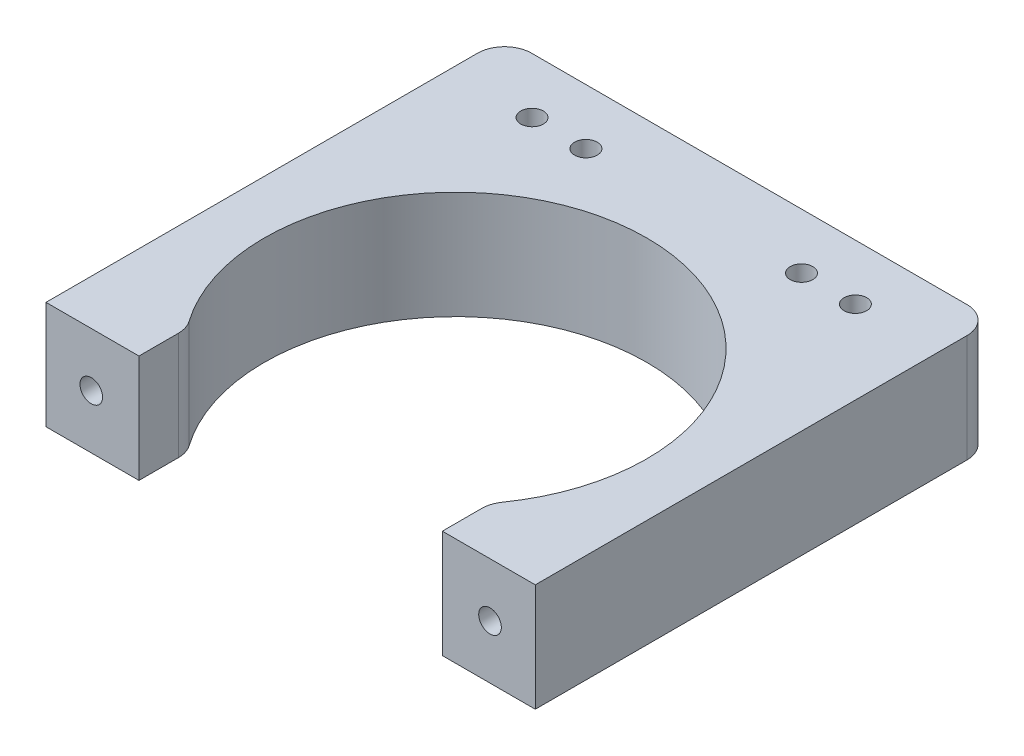
SolidWorks part; units mm, degrees
material "6061-T6 (SS)"
ref_plane "Front Plane" through (0, 0, 0) normal (0, 0, 1) x (1, 0, 0)
ref_plane "Top Plane" through (0, 0, 0) normal (0, 1, 0) x (1, 0, 0)
ref_plane "Right Plane" through (0, 0, 0) normal (1, 0, 0) x (0, 0, -1)
sketch "Sketch1" plane through (0, 0, 0) normal (0, 1, 0) x (1, 0, 0)
  line L0 (28.15, -42.55) -> (45.4, -42.55)
  line L1 (-45.4, 42.55) -> (45.4, 42.55)
  line L2 (-45.4, 42.55) -> (-45.4, -42.55)
  line L3 (-45.4, -42.55) -> (-28.15, -42.55)
  line L4 (45.4, 42.55) -> (45.4, -42.55)
  line L5 (-45.4, 42.55) -> (45.4, -42.55) construction
  line L6 (-45.4, -42.55) -> (45.4, 42.55) construction
  line L7 (-28.15, -42.55) -> (-28.15, -33.5793)
  line L8 (0, 0) -> (0, 42.55) construction
  line L9 (28.15, -42.55) -> (28.15, -33.5793)
  arc A0 (28.15, -33.5793) -> (-28.15, -33.5793) centre (0, -11.95) ccw
  point P0 (0, 0)
  dimension "D4" = 35.5
  dimension "D1" = 90.8
  dimension "D2" = 85.1
  dimension "D3" = 54.5
  dimension "D5" = 45.4
  dimension "D6" = 17.25
  dimension "D7" = 17.25
extrude "Boss-Extrude1" add sketch "Sketch1" along normal blind 20
sketch "Sketch3" plane through (0, 20, 0) normal (0, 1, 0) x (1, 0, 0)
  line L0 (45.4, 42.55) -> (-45.4, 42.55) construction
  line L1 (-45.4, 42.55) -> (-45.4, -42.55) construction
  line L2 (0, 0) -> (0, 50.4625) construction
  circle A0 centre (-30, 32.25) radius 2.1
  circle A1 centre (-20, 32.25) radius 2.1
  circle A2 centre (20, 32.25) radius 2.1
  circle A3 centre (30, 32.25) radius 2.1
  dimension "D1" = 4.2
  dimension "D2" = 10.3
  dimension "D3" = 15.4
  dimension "D4" = 10
extrude "Cut-Extrude1" cut sketch "Sketch3" against normal through all
sketch "Sketch4" plane through (0, 0, -42.55) normal (0, 0, -1) x (-1, 0, 0)
  line L0 (-45.4, 20) -> (-45.4, 0) construction
  line L1 (-45.4, 20) -> (45.4, 20) construction
  circle A0 centre (-30, 10) radius 2.1
  circle A1 centre (-10, 10) radius 2.1
  circle A2 centre (10, 10) radius 2.1
  circle A3 centre (30, 10) radius 2.1
  dimension "D1" = 4.2
  dimension "D2" = 15.4
  dimension "D3" = 10
  dimension "D4" = 4
hole_wizard "Ø4.2 (4.2) Diameter Hole1" positions "Sketch5" profile "Sketch6" hole size "Ø4.2" standard "ANSI Metric"
sketch "Sketch5" plane through (0, 0, -42.55) normal (0, 0, -1) x (-1, 0, 0)
  point P0 (-30, 10)
  point P3 (-10, 10)
  point P6 (10, 10)
  point P9 (30, 10)
sketch "Sketch6" plane through (30, 10, -42.55) normal (1, 0, 0) x (0, 1, 0)
  line L0 (0, 0) -> (0, 7.2618)
  line L1 (0, 7.2618) -> (2.1, 6)
  line L2 (2.1, 6) -> (2.1, 0)
  line L5 (2.1, 0) -> (0, 0)
  line L10 (0, 7.2618) -> (-2.1, 6) construction
  line L11 (0, -6.35) -> (0, 107.95) construction
  dimension "Hole Dia." = 4.2
  dimension "Hole Depth" = 6
  dimension "Drill Angle" = 118
sketch "Sketch14" plane through (-45.4, 0, 0) normal (-1, 0, 0) x (0, 0, 1)
  line L0 (-17.45, 20) -> (-17.45, 10)
  line L1 (-42.55, 20) -> (42.55, 20) construction
  line L3 (22.55, 20) -> (22.55, 10)
  line L4 (-42.55, 10) -> (22.55, 10)
  line L5 (-42.55, 20) -> (-42.55, 0) construction
  dimension "D1" = 25.1
  dimension "D2" = 40
hole_wizard "Ø4.2 (4.2) Diameter Hole4" positions "Sketch15" profile "Sketch16" hole size "Ø4.2" standard "ANSI Metric"
sketch "Sketch15" plane through (-45.4, 0, 0) normal (-1, 0, 0) x (0, 0, 1)
  point P0 (-17.45, 10)
  point P3 (22.55, 10)
sketch "Sketch16" plane through (-45.4, 10, -17.45) normal (0, 1, 0) x (0, 0, 1)
  line L0 (0, 0) -> (0, 7.2618)
  line L1 (0, 7.2618) -> (2.1, 6)
  line L2 (2.1, 6) -> (2.1, 0)
  line L5 (2.1, 0) -> (0, 0)
  line L10 (0, 7.2618) -> (-2.1, 6) construction
  line L11 (0, -6.35) -> (0, 107.95) construction
  dimension "Hole Dia." = 4.2
  dimension "Hole Depth" = 6
  dimension "Drill Angle" = 118
sketch "Sketch17" plane through (0, 0, 42.55) normal (0, 0, 1) x (1, 0, 0)
  line L0 (-37, 20) -> (-37, 10)
  line L1 (-45.4, 10) -> (17.9969, 10)
  line L2 (-45.4, 20) -> (-45.4, 10) construction
  line L3 (17.9969, 20) -> (17.9969, 0) construction
  line L4 (-45.4, 20) -> (-28.15, 20) construction
  dimension "D1" = 8.4
hole_wizard "Ø4.2 (4.2) Diameter Hole6" positions "Sketch19" profile "Sketch20" hole size "Ø4.2" standard "ANSI Metric"
sketch "Sketch19" plane through (0, 0, 42.55) normal (0, 0, 1) x (1, 0, 0)
  point P0 (-37, 10)
sketch "Sketch20" plane through (-37, 10, 42.55) normal (1, 0, 0) x (0, -1, 0)
  line L0 (0, 0) -> (0, 7.2618)
  line L1 (0, 7.2618) -> (2.1, 6)
  line L2 (2.1, 6) -> (2.1, 0)
  line L5 (2.1, 0) -> (0, 0)
  line L10 (0, 7.2618) -> (-2.1, 6) construction
  line L11 (0, -6.35) -> (0, 107.95) construction
  dimension "Hole Dia." = 4.2
  dimension "Hole Depth" = 6
  dimension "Drill Angle" = 118
mirror "Mirror2" about plane through (0, 0, 0) normal (1, 0, 0) of "Ø4.2 (4.2) Diameter Hole6"
fillet "Fillet2" radius 5 4 edges at (45.4, 10, -42.55) (-45.4, 10, -42.55) (28.15, 10, 33.5793) (-28.15, 10, 33.5793)
